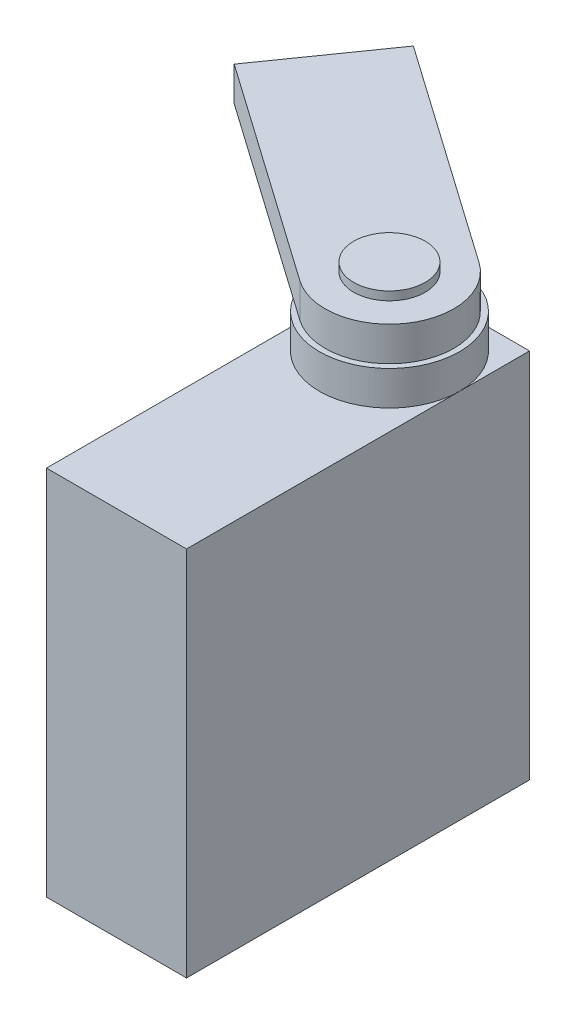
SolidWorks part; units mm, degrees
ref_plane "Front Plane" through (0, 0, 0) normal (0, 0, 1) x (1, 0, 0)
ref_plane "Top Plane" through (0, 0, 0) normal (0, 1, 0) x (1, 0, 0)
ref_plane "Right Plane" through (0, 0, 0) normal (1, 0, 0) x (0, 0, -1)
sketch "Sketch1" plane through (0, 0, 0) normal (0, 0, 1) x (1, 0, 0)
  line L1 (0, 0) -> (12.446, 0)
  line L2 (0, 0) -> (0, 33.02)
  line L3 (0, 33.02) -> (12.446, 33.02)
  line L4 (12.446, 0) -> (12.446, 33.02)
  dimension "D1" = 33.02
  dimension "D2" = 12.446
extrude "Boss-Extrude1" add sketch "Sketch1" along normal blind 30.48
sketch "Sketch3" plane through (0, 33.02, 0) normal (0, 1, 0) x (1, 0, 0)
  line L0 (6.223, 0) -> (6.223, -11.7908) construction
  line L1 (12.446, 0) -> (0, 0) construction
  circle A0 centre (6.223, -6.223) radius 6.223
  dimension "D1" = 12.446
  dimension "D2" = 6.223
extrude "Boss-Extrude2" add sketch "Sketch3" along normal blind 3.048
sketch "Sketch4" plane through (0, 36.068, 0) normal (0, 1, 0) x (1, 0, 0)
  circle A0 centre (6.223, -6.223) radius 6.223 construction
  circle A1 centre (6.223, -6.223) radius 3.175
  point P0 (6.223, -6.223)
  dimension "D1" = 6.35
extrude "Boss-Extrude3" add sketch "Sketch4" along normal blind 3.81
sketch "Sketch5" plane through (0, 36.068, 0) normal (0, 1, 0) x (1, 0, 0)
  line L1 (9.5067, -1.5455) -> (-10.0853, 12.2084)
  line L2 (-10.0853, 12.2084) -> (-16.6526, 2.8535)
  line L3 (-16.6526, 2.8535) -> (2.9393, -10.9005)
  circle A0 centre (6.223, -6.223) radius 3.175
  circle A1 centre (6.223, -6.223) radius 5.715
  circle M2 centre (6.223, -6.223) radius 3.175
  circle M3 centre (6.223, -6.223) radius 6.223
  dimension "D1" = 11.43
extrude "Boss-Extrude5" add sketch "Sketch5" along normal blind 3.048 contours A1 M2 | L2 L3 L1 M3 | A1 L1 L3 M3
